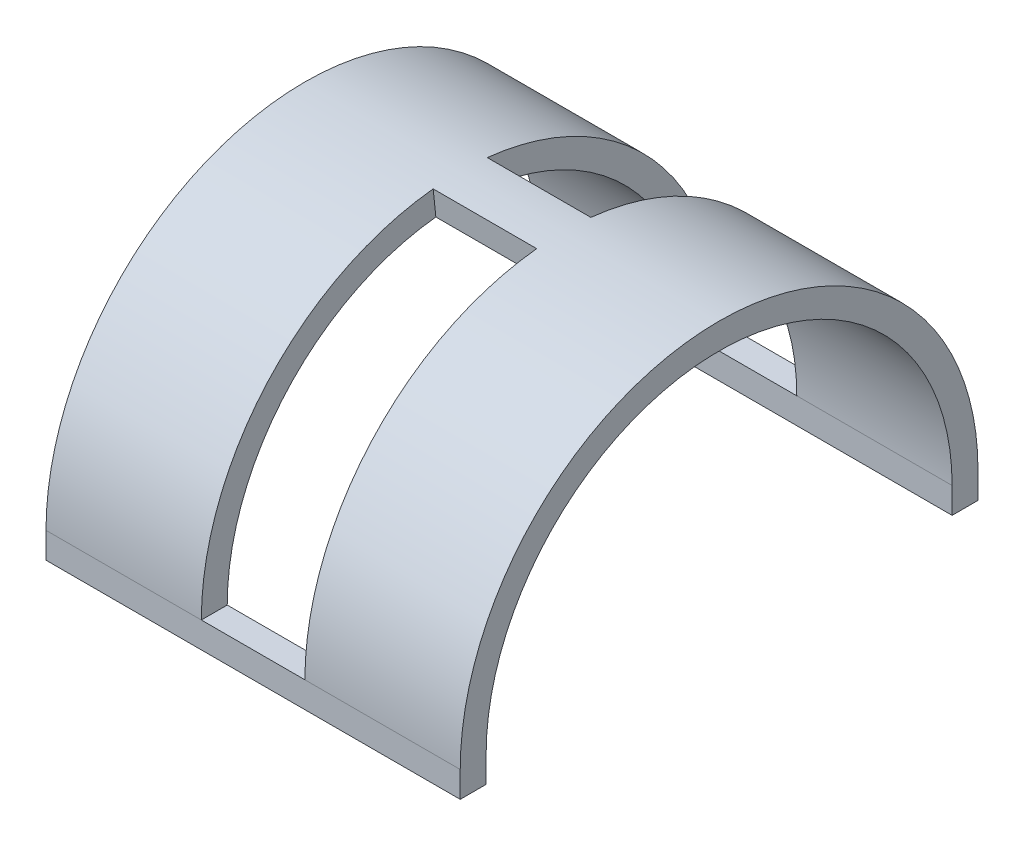
SolidWorks part; units mm, degrees
material "Copper"
ref_plane "Front Plane" through (0, 0, 0) normal (0, 0, 1) x (1, 0, 0)
ref_plane "Top Plane" through (0, 0, 0) normal (0, 1, 0) x (1, 0, 0)
ref_plane "Right Plane" through (0, 0, 0) normal (1, 0, 0) x (0, 0, -1)
sketch "Sketch1" plane through (0, 0, 0) normal (1, 0, 0) x (0, 0, -1)
  line L0 (-50, 0) -> (-45, 0)
  line L1 (45, 0) -> (50, 0)
  arc A0 (-50, 0) -> (50, 0) centre (0, 0) cw
  arc A1 (-45, 0) -> (45, 0) centre (0, 0) cw
  dimension "D1" = 5
  dimension "D2" = 100
extrude "Boss-Extrude3" add sketch "Sketch1" along normal blind 30
sketch "Sketch3" plane through (30, 0, 0) normal (1, 0, 0) x (0, 0, -1)
  line L0 (45, 0) -> (50, 0) construction
  line L1 (0, 0) -> (5.2264, 49.7261)
  line L2 (0, 0) -> (-5.2264, 49.7261)
  line L3 (0, 50) -> (0, 0) construction
  arc A0 (-50, 0) -> (50, 0) centre (0, 0) cw
  arc A1 (50, 0) -> (-50, 0) centre (0, 0) ccw construction
  arc A2 (-45, 0) -> (45, 0) centre (0, 0) cw
  arc M6 (50, 0) -> (-50, 0) centre (0, 0) ccw
  arc M8 (-45, 0) -> (45, 0) centre (0, 0) cw
  dimension "D3" = 6
  dimension "D4" = 6
  dimension "D5" = 10.4528
extrude "Boss-Extrude4" add sketch "Sketch3" along normal blind 10 contours L3 A0 L2 M8 | L3 A2 L1 M6
mirror "Mirror3" about plane through (40, 0, 0) normal (1, 0, 0) of bodies 104
sketch "Sketch4" plane through (0, 0, 0) normal (0, -1, 0) x (1, 0, 0)
  line L1 (0, 50) -> (80, 50)
  line L2 (0, 50) -> (0, 45)
  line L3 (0, 45) -> (80, 45)
  line L4 (80, 50) -> (80, 45)
  line L5 (80, -50) -> (0, -50)
  line L6 (80, -50) -> (80, -45)
  line L7 (80, -45) -> (0, -45)
  line L8 (0, -50) -> (0, -45)
extrude "Boss-Extrude5" add sketch "Sketch4" along normal blind 5
